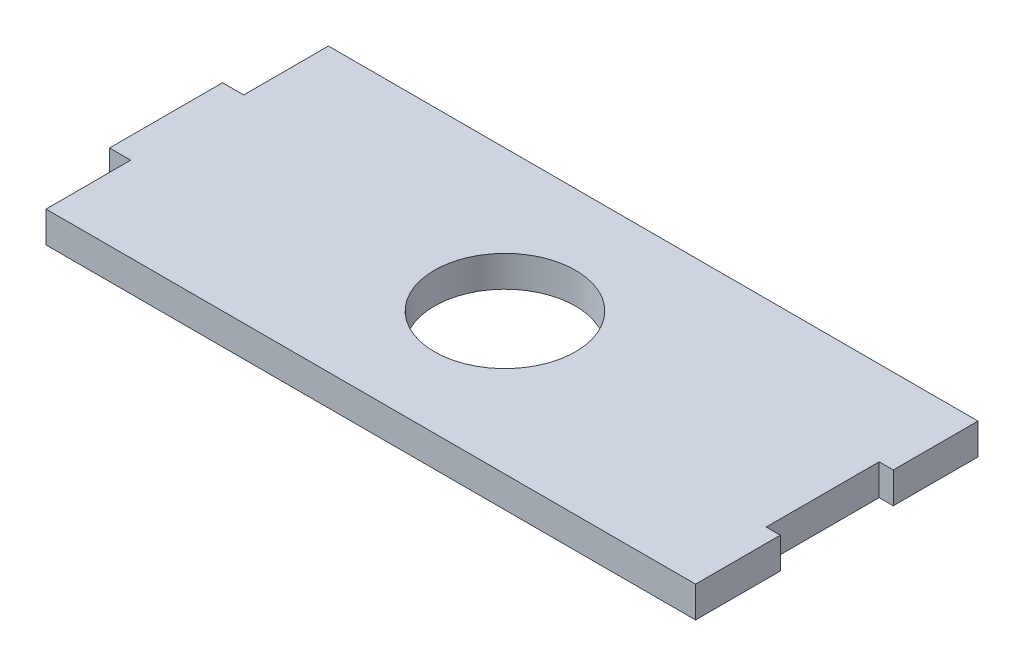
SolidWorks part; units mm, degrees
material "cardboard"
ref_plane "Front Plane" through (0, 0, 0) normal (0, 0, 1) x (1, 0, 0)
ref_plane "Top Plane" through (0, 0, 0) normal (0, 1, 0) x (1, 0, 0)
ref_plane "Right Plane" through (0, 0, 0) normal (1, 0, 0) x (0, 0, -1)
sketch "Sketch1" plane through (0, 0, 0) normal (0, 1, 0) x (1, 0, 0)
  line L0 (76.9454, 11.5977) -> (70.0953, 7.6428)
  line L1 (102.4454, -12.4023) -> (109.2956, -8.4474)
  line L2 (117.5953, 7.6428) -> (109.2956, 7.6428)
  line L3 (117.5953, -8.4474) -> (109.2956, -8.4474)
  line L4 (70.0953, 7.6428) -> (61.7956, 7.6428)
  line L5 (124.4454, 11.5977) -> (117.5953, 7.6428)
  line L6 (124.4454, -12.4023) -> (117.5953, -8.4474)
  line L7 (102.4454, 11.5977) -> (109.2956, 7.6428)
  line L8 (124.4454, 11.5977) -> (137.1954, 11.5977)
  line L9 (124.4454, -12.4023) -> (161.1954, -12.4023)
  line L10 (54.9454, 11.5977) -> (61.7956, 7.6428)
  line L11 (54.9454, -12.4023) -> (61.7956, -8.4474)
  line L12 (76.9454, -12.4023) -> (70.0953, -8.4474)
  line L13 (70.0953, -8.4474) -> (61.7956, -8.4474)
  line L14 (76.9454, 11.5977) -> (102.4454, 11.5977)
  line L15 (76.9454, -12.4023) -> (102.4454, -12.4023)
  line L16 (-12.8046, 77.3477) -> (-8.8496, 70.4976)
  line L17 (11.1954, 102.8477) -> (7.2405, 109.6979)
  line L18 (-8.8496, 117.9976) -> (-8.8496, 109.6979)
  line L19 (7.2405, 117.9976) -> (7.2405, 109.6979)
  line L20 (-8.8496, 70.4976) -> (-8.8496, 62.1979)
  line L21 (-12.8046, 124.8477) -> (-8.8496, 117.9976)
  line L22 (11.1954, 124.8477) -> (7.2405, 117.9976)
  line L23 (-12.8046, 102.8477) -> (-8.8496, 109.6979)
  line L24 (-12.8046, 124.8477) -> (-12.8046, 137.5977)
  line L25 (11.1954, 124.8477) -> (11.1954, 161.5977)
  line L26 (-12.8046, 55.3477) -> (-8.8496, 62.1979)
  line L27 (11.1954, 55.3477) -> (7.2405, 62.1979)
  line L28 (11.1954, 77.3477) -> (7.2405, 70.4976)
  line L29 (7.2405, 70.4976) -> (7.2405, 62.1979)
  line L30 (-12.8046, 77.3477) -> (-12.8046, 102.8477)
  line L31 (11.1954, 77.3477) -> (11.1954, 102.8477)
  line L32 (89.6954, 36.5977) -> (89.6954, 16.5977)
  line L33 (88.6954, 36.5977) -> (88.6954, 30.5977)
  line L34 (36.1954, 11.5977) -> (42.1954, 11.5977)
  line L35 (88.6954, 30.5977) -> (90.6954, 30.5977)
  line L36 (40.9454, 11.5977) -> (40.9454, 9.5977)
  line L37 (42.1954, 11.5977) -> (54.9454, 11.5977)
  line L38 (137.1954, 11.5977) -> (137.1954, -12.4023)
  line L39 (137.1954, 11.5977) -> (161.1954, 11.5977)
  line L40 (161.1954, 11.5977) -> (161.1954, 9.5977)
  line L41 (-29.301, 13.952) -> (-0.8046, -14.5444)
  line L42 (-29.301, 13.952) -> (-15.1588, 28.0941)
  line L43 (-0.8046, -14.5444) -> (13.3376, -0.4023)
  line L44 (-15.1588, 28.0941) -> (13.3376, -0.4023)
  line L45 (137.1954, 11.5977) -> (137.1954, 36.5977)
  line L46 (39.1954, 36.5977) -> (161.1954, 36.5977)
  line L47 (161.1954, 36.5977) -> (161.1954, 11.5977)
  line L48 (90.6954, 30.5977) -> (90.6954, 22.5977)
  line L49 (137.1954, 36.5977) -> (137.1954, 60.5977)
  line L50 (137.1954, 60.5977) -> (146.1954, 60.5977)
  line L51 (42.1954, 36.5977) -> (42.1954, 16.5977)
  line L52 (161.1954, 60.5977) -> (161.1954, 50.9197)
  line L53 (146.1954, 60.5977) -> (146.1954, 62.7977)
  line L54 (152.1954, 62.7977) -> (152.1954, 60.5977)
  line L55 (152.1954, 60.5977) -> (161.1954, 60.5977)
  line L56 (-59.8046, 137.5977) -> (-59.8046, 113.0977)
  line L57 (-39.8046, 113.0977) -> (-39.8046, 137.5977)
  line L58 (90.6954, 22.5977) -> (88.6954, 22.5977)
  line L59 (137.1954, -12.4023) -> (137.1954, -37.4023)
  line L60 (146.1954, -37.4023) -> (152.1954, -37.4023)
  line L61 (161.1954, -37.4023) -> (161.1954, -12.4023)
  line L62 (42.1954, -37.4023) -> (42.1954, -17.4023)
  line L63 (137.1954, -37.4023) -> (137.1954, -38.5823)
  line L64 (152.1954, -38.5823) -> (161.1954, -38.5823)
  line L65 (161.1954, -38.5823) -> (161.1954, -37.4023)
  line L66 (146.1954, -38.5823) -> (146.1954, -37.4023)
  line L67 (152.1954, -38.5823) -> (152.1954, -37.4023)
  line L68 (-38.9846, -138.4023) -> (-38.9846, -147.4023)
  line L69 (88.6954, 22.5977) -> (88.6954, 16.5977)
  line L70 (88.6954, 11.5977) -> (88.6954, 3.5977)
  line L71 (42.1954, -12.4023) -> (54.9454, -12.4023)
  line L72 (36.1954, -12.4023) -> (42.1954, -12.4023)
  line L73 (89.6692, 11.5977) -> (89.6692, -12.4023)
  line L74 (88.6954, 3.5977) -> (90.6954, 3.5977)
  line L75 (90.6954, 3.5977) -> (90.6954, -4.4023)
  line L76 (90.6954, -4.4023) -> (88.6954, -4.4023)
  line L77 (135.1954, 11.5977) -> (135.1954, 3.5977)
  line L78 (135.1954, 3.5977) -> (139.1954, 3.5977)
  line L79 (37.3754, 161.5977) -> (37.3754, 152.5977)
  line L80 (37.1954, 34.5977) -> (37.1954, 18.5977)
  line L81 (39.1954, 16.5977) -> (137.1954, 16.5977)
  line L82 (40.9454, 23.5977) -> (40.9454, 16.5977)
  line L83 (42.1954, 29.5977) -> (39.1954, 29.5977)
  line L84 (39.1954, 29.5977) -> (39.1954, 23.5977)
  line L85 (43.4454, 5.5977) -> (40.9454, 5.5977)
  line L86 (5.1954, -42.1523) -> (5.1954, -40.1523)
  line L87 (40.9454, -6.4023) -> (43.4454, -6.4023)
  line L88 (43.4454, 5.5977) -> (43.4454, -6.4023)
  line L89 (42.1954, 11.5977) -> (42.1954, 5.5977)
  line L90 (40.9454, 9.5977) -> (43.4454, 9.5977)
  line L91 (43.4454, 9.5977) -> (43.4454, 7.5977)
  line L92 (43.4454, 7.5977) -> (40.9454, 7.5977)
  line L93 (40.9454, 7.5977) -> (40.9454, 5.5977)
  line L94 (40.9454, -8.4023) -> (40.9454, -6.4023)
  line L95 (43.4454, -8.4023) -> (40.9454, -8.4023)
  line L96 (43.4454, -10.4023) -> (43.4454, -8.4023)
  line L97 (40.9454, -10.4023) -> (43.4454, -10.4023)
  line L98 (40.9454, -12.4023) -> (40.9454, -10.4023)
  line L99 (139.1954, 3.5977) -> (139.1954, -4.4023)
  line L100 (139.1954, -4.4023) -> (135.1954, -4.4023)
  line L101 (135.1954, -4.4023) -> (135.1954, -12.4023)
  line L102 (137.1954, 13.5977) -> (145.1954, 13.5977)
  line L103 (145.1954, 13.5977) -> (145.1954, 9.5977)
  line L104 (145.1954, 9.5977) -> (153.1954, 9.5977)
  line L105 (153.1954, 9.5977) -> (153.1954, 13.5977)
  line L106 (153.1954, 13.5977) -> (161.1954, 13.5977)
  line L107 (135.6954, 36.5977) -> (135.6954, 30.5977)
  line L108 (135.6954, 30.5977) -> (138.6954, 30.5977)
  line L109 (138.6954, 30.5977) -> (138.6954, 22.5977)
  line L110 (138.6954, 22.5977) -> (135.6954, 22.5977)
  line L111 (135.6954, 22.5977) -> (135.6954, 16.5977)
  line L112 (88.6954, -4.4023) -> (88.6954, -12.4023)
  line L113 (88.6954, -23.4023) -> (88.6954, -17.4023)
  line L114 (89.6954, -37.4023) -> (89.6954, -17.4023)
  line L115 (90.6954, -23.4023) -> (88.6954, -23.4023)
  line L116 (90.6954, -31.4023) -> (90.6954, -23.4023)
  line L117 (153.1954, -14.4023) -> (161.1954, -14.4023)
  line L118 (153.1954, -10.4023) -> (153.1954, -14.4023)
  line L119 (145.1954, -10.4023) -> (153.1954, -10.4023)
  line L120 (145.1954, -14.4023) -> (145.1954, -10.4023)
  line L121 (137.1954, -14.4023) -> (145.1954, -14.4023)
  line L122 (135.6954, -23.4023) -> (135.6954, -17.4023)
  line L123 (138.6954, -23.4023) -> (135.6954, -23.4023)
  line L124 (40.9454, 36.5977) -> (40.9454, 29.5977)
  line L125 (42.1954, 23.5977) -> (39.1954, 23.5977)
  line L126 (137.1954, -37.4023) -> (39.1954, -37.4023)
  line L127 (37.1954, -35.4023) -> (37.1954, -19.4023)
  line L128 (39.1954, -17.4023) -> (137.1954, -17.4023)
  line L129 (138.6954, -31.4023) -> (138.6954, -23.4023)
  line L130 (135.6954, -31.4023) -> (138.6954, -31.4023)
  line L131 (135.6954, -37.4023) -> (135.6954, -31.4023)
  line L132 (88.6954, -31.4023) -> (90.6954, -31.4023)
  line L133 (88.6954, -37.4023) -> (88.6954, -31.4023)
  line L134 (137.1954, 38.5977) -> (145.1954, 38.5977)
  line L135 (145.1954, 38.5977) -> (145.1954, 34.5977)
  line L136 (145.1954, 34.5977) -> (153.1954, 34.5977)
  line L137 (153.1954, 34.5977) -> (153.1954, 38.5977)
  line L138 (153.1954, 38.5977) -> (161.1954, 38.5977)
  line L139 (-45.3046, 133.3477) -> (-45.3046, 117.3477)
  line L140 (-56.8046, 133.3477) -> (-54.3046, 133.3477)
  line L141 (-56.8046, 133.3477) -> (-56.8046, 117.3477)
  line L142 (-56.8046, 117.3477) -> (-54.3046, 117.3477)
  line L143 (-54.3046, 133.3477) -> (-54.3046, 117.3477)
  line L144 (40.9454, -24.4023) -> (40.9454, -17.4023)
  line L145 (42.1954, -24.4023) -> (39.1954, -24.4023)
  line L146 (39.1954, -30.4023) -> (39.1954, -24.4023)
  line L147 (42.1954, -30.4023) -> (39.1954, -30.4023)
  line L148 (40.9454, -37.4023) -> (40.9454, -30.4023)
  line L149 (196.1954, 4.5977) -> (196.1954, -5.4023)
  line L150 (191.1954, 9.5977) -> (161.1954, 9.5977)
  line L151 (191.1954, -10.4023) -> (161.1954, -10.4023)
  line L152 (191.1954, 9.5977) -> (196.1954, 4.5977)
  line L153 (196.1954, -5.4023) -> (191.1954, -10.4023)
  line L154 (161.1954, -10.4023) -> (161.1954, -12.4023)
  line L155 (137.1954, 62.7977) -> (146.1954, 62.7977)
  line L156 (137.1954, 62.7977) -> (137.1954, 64.7977)
  line L157 (137.1954, 64.7977) -> (161.1954, 64.7977)
  line L158 (161.1954, 64.7977) -> (161.1954, 62.7977)
  line L159 (152.1954, 62.7977) -> (161.1954, 62.7977)
  line L160 (-42.8046, 117.3477) -> (-45.3046, 117.3477)
  line L161 (-42.8046, 133.3477) -> (-42.8046, 117.3477)
  line L162 (-42.8046, 133.3477) -> (-45.3046, 133.3477)
  line L163 (154.5954, 50.9197) -> (161.1954, 50.9197)
  line L164 (154.5954, 50.9197) -> (154.5954, 46.4197)
  line L165 (154.5954, 46.4197) -> (161.1954, 46.4197)
  line L166 (161.1954, 46.4197) -> (161.1954, 36.5977)
  line L167 (11.1954, -78.1523) -> (7.2405, -71.3021)
  line L168 (-12.8046, -103.6523) -> (-8.8496, -110.5024)
  line L169 (7.2405, -118.8021) -> (7.2405, -110.5024)
  line L170 (11.1954, -37.4023) -> (11.1954, -43.4023)
  line L171 (11.1954, -42.1523) -> (9.1954, -42.1523)
  line L172 (11.1954, -43.4023) -> (11.1954, -56.1523)
  line L173 (-8.8496, -118.8021) -> (-8.8496, -110.5024)
  line L174 (7.2405, -71.3021) -> (7.2405, -63.0024)
  line L175 (11.1954, -125.6523) -> (7.2405, -118.8021)
  line L176 (-12.8046, -125.6523) -> (-8.8496, -118.8021)
  line L177 (11.1954, -103.6523) -> (7.2405, -110.5024)
  line L178 (11.1954, -125.6523) -> (11.1954, -138.4023)
  line L179 (-12.8046, -125.6523) -> (-12.8046, -162.4023)
  line L180 (11.1954, -56.1523) -> (7.2405, -63.0024)
  line L181 (-12.8046, -56.1523) -> (-8.8496, -63.0024)
  line L182 (36.1954, -43.4023) -> (16.1954, -43.4023)
  line L183 (-12.8046, -78.1523) -> (-8.8496, -71.3021)
  line L184 (-8.8496, -71.3021) -> (-8.8496, -63.0024)
  line L185 (11.1954, -78.1523) -> (11.1954, -103.6523)
  line L186 (-12.8046, -78.1523) -> (-12.8046, -103.6523)
  line L187 (36.1954, -90.9023) -> (16.1954, -90.9023)
  line L188 (36.1954, -89.9023) -> (30.1954, -89.9023)
  line L189 (30.1954, -89.9023) -> (30.1954, -91.9023)
  line L190 (11.1954, -138.4023) -> (-12.8046, -138.4023)
  line L191 (11.1954, -138.4023) -> (11.1954, -162.4023)
  line L192 (11.1954, -162.4023) -> (9.1954, -162.4023)
  line L193 (11.1954, -138.4023) -> (36.1954, -138.4023)
  line L194 (36.1954, -40.4023) -> (36.1954, -162.4023)
  line L195 (-37.8046, -43.4023) -> (-17.8046, -43.4023)
  line L196 (36.1954, -162.4023) -> (11.1954, -162.4023)
  line L197 (30.1954, -91.9023) -> (22.1954, -91.9023)
  line L198 (36.1954, -138.4023) -> (60.1954, -138.4023)
  line L199 (60.1954, -138.4023) -> (60.1954, -147.4023)
  line L200 (60.1954, -162.4023) -> (50.5174, -162.4023)
  line L201 (60.1954, -147.4023) -> (62.3954, -147.4023)
  line L202 (62.3954, -153.4023) -> (60.1954, -153.4023)
  line L203 (60.1954, -153.4023) -> (60.1954, -162.4023)
  line L204 (-12.8046, -43.4023) -> (-12.8046, -56.1523)
  line L205 (-12.8046, -37.4023) -> (-12.8046, -43.4023)
  line L206 (22.1954, -91.9023) -> (22.1954, -89.9023)
  line L207 (-12.8046, -138.4023) -> (-37.8046, -138.4023)
  line L208 (-37.8046, -147.4023) -> (-37.8046, -153.4023)
  line L209 (37.3754, 146.5977) -> (37.3754, 137.5977)
  line L210 (34.1954, -38.4023) -> (18.1954, -38.4023)
  line L211 (16.1954, -40.4023) -> (16.1954, -138.4023)
  line L212 (23.1954, -42.1523) -> (16.1954, -42.1523)
  line L213 (29.1954, -43.4023) -> (29.1954, -40.4023)
  line L214 (29.1954, -40.4023) -> (23.1954, -40.4023)
  line L215 (5.1954, -44.6523) -> (5.1954, -42.1523)
  line L216 (-37.8046, -162.4023) -> (-12.8046, -162.4023)
  line L217 (-6.8046, -42.1523) -> (-6.8046, -44.6523)
  line L218 (5.1954, -44.6523) -> (-6.8046, -44.6523)
  line L219 (11.1954, -43.4023) -> (5.1954, -43.4023)
  line L220 (9.1954, -42.1523) -> (9.1954, -44.6523)
  line L221 (9.1954, -44.6523) -> (7.1954, -44.6523)
  line L222 (7.1954, -44.6523) -> (7.1954, -42.1523)
  line L223 (7.1954, -42.1523) -> (5.1954, -42.1523)
  line L224 (-8.8046, -42.1523) -> (-6.8046, -42.1523)
  line L225 (-8.8046, -44.6523) -> (-8.8046, -42.1523)
  line L226 (-10.8046, -44.6523) -> (-8.8046, -44.6523)
  line L227 (-10.8046, -42.1523) -> (-10.8046, -44.6523)
  line L228 (-12.8046, -42.1523) -> (-10.8046, -42.1523)
  line L229 (-37.8046, -138.4023) -> (-38.9846, -138.4023)
  line L230 (-38.9846, -153.4023) -> (-38.9846, -162.4023)
  line L231 (-38.9846, -162.4023) -> (-37.8046, -162.4023)
  line L232 (-38.9846, -147.4023) -> (-37.8046, -147.4023)
  line L233 (-38.9846, -153.4023) -> (-37.8046, -153.4023)
  line L234 (-162.8046, 37.7777) -> (-153.8046, 37.7777)
  line L235 (22.1954, -89.9023) -> (16.1954, -89.9023)
  line L236 (11.1954, -89.9023) -> (3.1954, -89.9023)
  line L237 (11.1954, -90.8761) -> (-12.8046, -90.8761)
  line L238 (3.1954, -89.9023) -> (3.1954, -91.9023)
  line L239 (3.1954, -91.9023) -> (-4.8046, -91.9023)
  line L240 (-4.8046, -91.9023) -> (-4.8046, -89.9023)
  line L241 (11.1954, -136.4023) -> (3.1954, -136.4023)
  line L242 (3.1954, -136.4023) -> (3.1954, -140.4023)
  line L243 (3.1954, -140.4023) -> (-4.8046, -140.4023)
  line L244 (-4.8046, -140.4023) -> (-4.8046, -136.4023)
  line L245 (-4.8046, -136.4023) -> (-12.8046, -136.4023)
  line L246 (13.1954, -138.4023) -> (13.1954, -146.4023)
  line L247 (13.1954, -146.4023) -> (9.1954, -146.4023)
  line L248 (9.1954, -146.4023) -> (9.1954, -154.4023)
  line L249 (9.1954, -154.4023) -> (13.1954, -154.4023)
  line L250 (13.1954, -154.4023) -> (13.1954, -162.4023)
  line L251 (36.1954, -136.9023) -> (30.1954, -136.9023)
  line L252 (30.1954, -136.9023) -> (30.1954, -139.9023)
  line L253 (30.1954, -139.9023) -> (22.1954, -139.9023)
  line L254 (36.1954, -42.1523) -> (29.1954, -42.1523)
  line L255 (23.1954, -43.4023) -> (23.1954, -40.4023)
  line L256 (-37.8046, -138.4023) -> (-37.8046, -40.4023)
  line L257 (-35.8046, -38.4023) -> (-19.8046, -38.4023)
  line L258 (-17.8046, -40.4023) -> (-17.8046, -138.4023)
  line L259 (22.1954, -139.9023) -> (22.1954, -136.9023)
  line L260 (22.1954, -136.9023) -> (16.1954, -136.9023)
  line L261 (-4.8046, -89.9023) -> (-12.8046, -89.9023)
  line L262 (-23.8046, -89.9023) -> (-17.8046, -89.9023)
  line L263 (-37.8046, -90.9023) -> (-17.8046, -90.9023)
  line L264 (-23.8046, -91.9023) -> (-23.8046, -89.9023)
  line L265 (-31.8046, -91.9023) -> (-23.8046, -91.9023)
  line L266 (-14.8046, -154.4023) -> (-14.8046, -162.4023)
  line L267 (-10.8046, -154.4023) -> (-14.8046, -154.4023)
  line L268 (-10.8046, -146.4023) -> (-10.8046, -154.4023)
  line L269 (-14.8046, -146.4023) -> (-10.8046, -146.4023)
  line L270 (-14.8046, -138.4023) -> (-14.8046, -146.4023)
  line L271 (-23.8046, -136.9023) -> (-17.8046, -136.9023)
  line L272 (-23.8046, -139.9023) -> (-23.8046, -136.9023)
  line L273 (-31.8046, -139.9023) -> (-23.8046, -139.9023)
  line L274 (-24.8046, -42.1523) -> (-17.8046, -42.1523)
  line L275 (-24.8046, -43.4023) -> (-24.8046, -40.4023)
  line L276 (-30.8046, -40.4023) -> (-24.8046, -40.4023)
  line L277 (-30.8046, -43.4023) -> (-30.8046, -40.4023)
  line L278 (-37.8046, -42.1523) -> (-30.8046, -42.1523)
  line L279 (-31.8046, -136.9023) -> (-31.8046, -139.9023)
  line L280 (-37.8046, -136.9023) -> (-31.8046, -136.9023)
  line L281 (-31.8046, -89.9023) -> (-31.8046, -91.9023)
  line L282 (-37.8046, -89.9023) -> (-31.8046, -89.9023)
  line L283 (38.1954, -138.4023) -> (38.1954, -146.4023)
  line L284 (38.1954, -146.4023) -> (34.1954, -146.4023)
  line L285 (34.1954, -146.4023) -> (34.1954, -154.4023)
  line L286 (34.1954, -154.4023) -> (38.1954, -154.4023)
  line L287 (38.1954, -154.4023) -> (38.1954, -162.4023)
  line L288 (4.1954, -197.4023) -> (-5.8046, -197.4023)
  line L289 (9.1954, -192.4023) -> (9.1954, -162.4023)
  line L290 (-10.8046, -192.4023) -> (-10.8046, -162.4023)
  line L291 (9.1954, -192.4023) -> (4.1954, -197.4023)
  line L292 (-5.8046, -197.4023) -> (-10.8046, -192.4023)
  line L293 (-10.8046, -162.4023) -> (-12.8046, -162.4023)
  line L294 (62.3954, -138.4023) -> (62.3954, -147.4023)
  line L295 (62.3954, -138.4023) -> (64.3954, -138.4023)
  line L296 (64.3954, -138.4023) -> (64.3954, -162.4023)
  line L297 (64.3954, -162.4023) -> (62.3954, -162.4023)
  line L298 (62.3954, -153.4023) -> (62.3954, -162.4023)
  line L299 (-37.8046, -12.4023) -> (-43.8046, -12.4023)
  line L300 (-42.5546, -12.4023) -> (-42.5546, -10.4023)
  line L301 (-43.8046, -12.4023) -> (-56.5546, -12.4023)
  line L302 (50.5174, -155.8023) -> (50.5174, -162.4023)
  line L303 (50.5174, -155.8023) -> (46.0174, -155.8023)
  line L304 (-43.8046, -37.4023) -> (-43.8046, -17.4023)
  line L305 (46.0174, -155.8023) -> (46.0174, -162.4023)
  line L306 (46.0174, -162.4023) -> (36.1954, -162.4023)
  line L307 (-78.5546, -12.4023) -> (-71.7044, -8.4474)
  line L308 (-104.0546, 11.5977) -> (-110.9047, 7.6428)
  line L309 (-119.2044, -8.4474) -> (-110.9047, -8.4474)
  line L310 (-119.2044, 7.6428) -> (-110.9047, 7.6428)
  line L311 (-71.7044, -8.4474) -> (-63.4047, -8.4474)
  line L312 (-126.0546, -12.4023) -> (-119.2044, -8.4474)
  line L313 (-126.0546, 11.5977) -> (-119.2044, 7.6428)
  line L314 (-104.0546, -12.4023) -> (-110.9047, -8.4474)
  line L315 (-126.0546, -12.4023) -> (-138.8046, -12.4023)
  line L316 (-43.8046, 36.5977) -> (-43.8046, 16.5977)
  line L317 (-126.0546, 11.5977) -> (-162.8046, 11.5977)
  line L318 (-56.5546, -12.4023) -> (-63.4047, -8.4474)
  line L319 (-56.5546, 11.5977) -> (-63.4047, 7.6428)
  line L320 (-78.5546, 11.5977) -> (-71.7044, 7.6428)
  line L321 (-71.7044, 7.6428) -> (-63.4047, 7.6428)
  line L322 (-78.5546, -12.4023) -> (-104.0546, -12.4023)
  line L323 (-78.5546, 11.5977) -> (-104.0546, 11.5977)
  line L324 (-91.3046, -37.4023) -> (-91.3046, -17.4023)
  line L325 (-43.8046, 11.5977) -> (-56.5546, 11.5977)
  line L326 (-37.8046, 11.5977) -> (-43.8046, 11.5977)
  line L327 (-90.3046, -37.4023) -> (-90.3046, -31.4023)
  line L328 (-90.3046, -31.4023) -> (-92.3046, -31.4023)
  line L329 (-138.8046, -12.4023) -> (-138.8046, 11.5977)
  line L330 (-138.8046, -12.4023) -> (-162.8046, -12.4023)
  line L331 (-162.8046, -12.4023) -> (-162.8046, -10.4023)
  line L332 (-138.8046, -12.4023) -> (-138.8046, -37.4023)
  line L333 (137.1954, -38.5823) -> (146.1954, -38.5823)
  line L334 (-38.8046, -35.4023) -> (-38.8046, -19.4023)
  line L335 (-40.8046, -17.4023) -> (-138.8046, -17.4023)
  line L336 (-42.5546, -24.4023) -> (-42.5546, -17.4023)
  line L337 (-43.8046, -30.4023) -> (-40.8046, -30.4023)
  line L338 (-40.8046, -30.4023) -> (-40.8046, -24.4023)
  line L339 (-45.0546, -6.4023) -> (-42.5546, -6.4023)
  line L340 (-40.8046, -37.4023) -> (-162.8046, -37.4023)
  line L341 (-42.5546, 5.5977) -> (-45.0546, 5.5977)
  line L342 (-45.0546, -6.4023) -> (-45.0546, 5.5977)
  line L343 (-43.8046, -12.4023) -> (-43.8046, -6.4023)
  line L344 (-42.5546, -10.4023) -> (-45.0546, -10.4023)
  line L345 (-45.0546, -10.4023) -> (-45.0546, -8.4023)
  line L346 (-45.0546, -8.4023) -> (-42.5546, -8.4023)
  line L347 (-42.5546, -8.4023) -> (-42.5546, -6.4023)
  line L348 (-42.5546, 7.5977) -> (-42.5546, 5.5977)
  line L349 (-45.0546, 7.5977) -> (-42.5546, 7.5977)
  line L350 (-45.0546, 9.5977) -> (-45.0546, 7.5977)
  line L351 (-42.5546, 9.5977) -> (-45.0546, 9.5977)
  line L352 (-42.5546, 11.5977) -> (-42.5546, 9.5977)
  line L353 (-162.8046, -37.4023) -> (-162.8046, -12.4023)
  line L354 (-92.3046, -31.4023) -> (-92.3046, -23.4023)
  line L355 (-138.8046, -37.4023) -> (-138.8046, -61.4023)
  line L356 (-138.8046, -61.4023) -> (-147.8046, -61.4023)
  line L357 (-162.8046, -61.4023) -> (-162.8046, -51.7243)
  line L358 (-147.8046, -61.4023) -> (-147.8046, -63.6023)
  line L359 (-153.8046, -63.6023) -> (-153.8046, -61.4023)
  line L360 (-153.8046, -61.4023) -> (-162.8046, -61.4023)
  line L361 (-92.3046, -23.4023) -> (-90.3046, -23.4023)
  line L362 (-138.8046, 11.5977) -> (-138.8046, 36.5977)
  line L363 (-147.8046, 36.5977) -> (-153.8046, 36.5977)
  line L364 (-162.8046, 36.5977) -> (-162.8046, 11.5977)
  line L365 (-138.8046, 36.5977) -> (-138.8046, 37.7777)
  line L366 (-162.8046, 37.7777) -> (-162.8046, 36.5977)
  line L367 (-147.8046, 37.7777) -> (-147.8046, 36.5977)
  line L368 (-153.8046, 37.7777) -> (-153.8046, 36.5977)
  line L369 (-147.8046, 37.7777) -> (-138.8046, 37.7777)
  line L370 (-90.3046, -23.4023) -> (-90.3046, -17.4023)
  line L371 (-90.3046, -12.4023) -> (-90.3046, -4.4023)
  line L372 (-91.2784, -12.4023) -> (-91.2784, 11.5977)
  line L373 (-90.3046, -4.4023) -> (-92.3046, -4.4023)
  line L374 (-42.5546, -37.4023) -> (-42.5546, -30.4023)
  line L375 (-43.8046, -24.4023) -> (-40.8046, -24.4023)
  line L376 (-138.8046, 36.5977) -> (-40.8046, 36.5977)
  line L377 (-38.8046, 34.5977) -> (-38.8046, 18.5977)
  line L378 (-40.8046, 16.5977) -> (-138.8046, 16.5977)
  line L379 (-92.3046, -4.4023) -> (-92.3046, 3.5977)
  line L380 (-92.3046, 3.5977) -> (-90.3046, 3.5977)
  line L381 (-136.8046, -12.4023) -> (-136.8046, -4.4023)
  line L382 (-136.8046, -4.4023) -> (-140.8046, -4.4023)
  line L383 (-140.8046, -4.4023) -> (-140.8046, 3.5977)
  line L384 (-140.8046, 3.5977) -> (-136.8046, 3.5977)
  line L385 (-136.8046, 3.5977) -> (-136.8046, 11.5977)
  line L386 (-138.8046, -14.4023) -> (-146.8046, -14.4023)
  line L387 (-146.8046, -14.4023) -> (-146.8046, -10.4023)
  line L388 (-146.8046, -10.4023) -> (-154.8046, -10.4023)
  line L389 (-154.8046, -10.4023) -> (-154.8046, -14.4023)
  line L390 (-154.8046, -14.4023) -> (-162.8046, -14.4023)
  line L391 (-137.3046, -37.4023) -> (-137.3046, -31.4023)
  line L392 (-37.8046, 90.0977) -> (-17.8046, 90.0977)
  line L393 (-37.8046, 89.0977) -> (-31.8046, 89.0977)
  line L394 (-42.5546, 23.5977) -> (-42.5546, 16.5977)
  line L395 (-43.8046, 23.5977) -> (-40.8046, 23.5977)
  line L396 (-40.8046, 29.5977) -> (-40.8046, 23.5977)
  line L397 (-43.8046, 29.5977) -> (-40.8046, 29.5977)
  line L398 (-42.5546, 36.5977) -> (-42.5546, 29.5977)
  line L399 (-137.3046, -31.4023) -> (-140.3046, -31.4023)
  line L400 (-140.3046, -31.4023) -> (-140.3046, -23.4023)
  line L401 (-140.3046, -23.4023) -> (-137.3046, -23.4023)
  line L402 (-137.3046, -23.4023) -> (-137.3046, -17.4023)
  line L403 (-90.3046, 3.5977) -> (-90.3046, 11.5977)
  line L404 (-90.3046, 22.5977) -> (-90.3046, 16.5977)
  line L405 (-91.3046, 36.5977) -> (-91.3046, 16.5977)
  line L406 (-92.3046, 22.5977) -> (-90.3046, 22.5977)
  line L407 (-92.3046, 30.5977) -> (-92.3046, 22.5977)
  line L408 (-154.8046, 13.5977) -> (-162.8046, 13.5977)
  line L409 (-154.8046, 9.5977) -> (-154.8046, 13.5977)
  line L410 (-146.8046, 9.5977) -> (-154.8046, 9.5977)
  line L411 (-146.8046, 13.5977) -> (-146.8046, 9.5977)
  line L412 (-138.8046, 13.5977) -> (-146.8046, 13.5977)
  line L413 (-137.3046, 22.5977) -> (-137.3046, 16.5977)
  line L414 (-140.3046, 22.5977) -> (-137.3046, 22.5977)
  line L415 (-140.3046, 30.5977) -> (-140.3046, 22.5977)
  line L416 (-137.3046, 30.5977) -> (-140.3046, 30.5977)
  line L417 (-137.3046, 36.5977) -> (-137.3046, 30.5977)
  line L418 (-90.3046, 30.5977) -> (-92.3046, 30.5977)
  line L419 (-90.3046, 36.5977) -> (-90.3046, 30.5977)
  line L420 (-138.8046, -39.4023) -> (-146.8046, -39.4023)
  line L421 (-146.8046, -39.4023) -> (-146.8046, -35.4023)
  line L422 (-146.8046, -35.4023) -> (-154.8046, -35.4023)
  line L423 (-154.8046, -35.4023) -> (-154.8046, -39.4023)
  line L424 (-154.8046, -39.4023) -> (-162.8046, -39.4023)
  line L425 (-12.8046, 41.3477) -> (-10.8046, 41.3477)
  line L426 (-31.8046, 89.0977) -> (-31.8046, 91.0977)
  line L427 (-12.8046, 137.5977) -> (11.1954, 137.5977)
  line L428 (-12.8046, 137.5977) -> (-12.8046, 161.5977)
  line L429 (-12.8046, 161.5977) -> (-10.8046, 161.5977)
  line L430 (-12.8046, 137.5977) -> (-37.8046, 137.5977)
  line L431 (-37.8046, 137.5977) -> (-37.8046, 161.5977)
  line L432 (-37.8046, 161.5977) -> (-12.8046, 161.5977)
  line L433 (-37.8046, 137.5977) -> (-37.8046, 42.5977)
  line L434 (-37.8046, 42.5977) -> (-17.8046, 42.5977)
  line L435 (-17.8046, 42.5977) -> (-17.8046, 137.5977)
  line L436 (-31.8046, 91.0977) -> (-23.8046, 91.0977)
  line L437 (-37.8046, 137.5977) -> (-61.8046, 137.5977)
  line L438 (-61.8046, 137.5977) -> (-61.8046, 146.5977)
  line L439 (-61.8046, 161.5977) -> (-52.1265, 161.5977)
  line L440 (-61.8046, 146.5977) -> (-64.0046, 146.5977)
  line L441 (-64.0046, 152.5977) -> (-61.8046, 152.5977)
  line L442 (-61.8046, 152.5977) -> (-61.8046, 161.5977)
  line L443 (-59.8046, 113.0977) -> (-39.8046, 113.0977)
  line L444 (36.1954, 42.5977) -> (16.1954, 42.5977)
  line L445 (-23.8046, 91.0977) -> (-23.8046, 89.0977)
  line L446 (36.1954, 137.5977) -> (36.1954, 42.5977)
  line L447 (16.1954, 42.5977) -> (16.1954, 137.5977)
  line L448 (11.1954, 137.5977) -> (36.1954, 137.5977)
  line L449 (36.1954, 146.5977) -> (36.1954, 152.5977)
  line L450 (36.1954, 161.5977) -> (11.1954, 161.5977)
  line L451 (11.1954, 36.5977) -> (11.1954, 55.3477)
  line L452 (36.1954, 137.5977) -> (37.3754, 137.5977)
  line L453 (37.3754, 161.5977) -> (36.1954, 161.5977)
  line L454 (37.3754, 146.5977) -> (36.1954, 146.5977)
  line L455 (37.3754, 152.5977) -> (36.1954, 152.5977)
  line L456 (-37.8046, 42.5977) -> (-37.8046, 39.5977)
  line L457 (-35.8046, 37.5977) -> (-19.8046, 37.5977)
  line L458 (-17.8046, 39.5977) -> (-17.8046, 42.5977)
  line L459 (34.1954, 37.5977) -> (18.1954, 37.5977)
  line L460 (16.1954, 39.5977) -> (16.1954, 42.5977)
  line L461 (-6.8046, 43.8477) -> (-6.8046, 41.3477)
  line L462 (-23.8046, 89.0977) -> (-17.8046, 89.0977)
  line L463 (5.1954, 41.3477) -> (5.1954, 43.8477)
  line L464 (-6.8046, 43.8477) -> (5.1954, 43.8477)
  line L465 (-12.8046, 42.5977) -> (-6.8046, 42.5977)
  line L466 (-10.8046, 41.3477) -> (-10.8046, 43.8477)
  line L467 (-10.8046, 43.8477) -> (-8.8046, 43.8477)
  line L468 (-8.8046, 43.8477) -> (-8.8046, 41.3477)
  line L469 (-8.8046, 41.3477) -> (-6.8046, 41.3477)
  line L470 (7.1954, 41.3477) -> (5.1954, 41.3477)
  line L471 (7.1954, 43.8477) -> (7.1954, 41.3477)
  line L472 (9.1954, 43.8477) -> (7.1954, 43.8477)
  line L473 (9.1954, 41.3477) -> (9.1954, 43.8477)
  line L474 (11.1954, 41.3477) -> (9.1954, 41.3477)
  line L475 (-12.8046, 89.0977) -> (-4.8046, 89.0977)
  line L476 (-12.8046, 90.0715) -> (11.1954, 90.0715)
  line L477 (-4.8046, 89.0977) -> (-4.8046, 91.0977)
  line L478 (-4.8046, 91.0977) -> (3.1954, 91.0977)
  line L479 (3.1954, 91.0977) -> (3.1954, 89.0977)
  line L480 (-12.8046, 135.5977) -> (-4.8046, 135.5977)
  line L481 (-4.8046, 135.5977) -> (-4.8046, 139.5977)
  line L482 (-4.8046, 139.5977) -> (3.1954, 139.5977)
  line L483 (3.1954, 139.5977) -> (3.1954, 135.5977)
  line L484 (3.1954, 135.5977) -> (11.1954, 135.5977)
  line L485 (-14.8046, 137.5977) -> (-14.8046, 145.5977)
  line L486 (-14.8046, 145.5977) -> (-10.8046, 145.5977)
  line L487 (-10.8046, 145.5977) -> (-10.8046, 153.5977)
  line L488 (-10.8046, 153.5977) -> (-14.8046, 153.5977)
  line L489 (-14.8046, 153.5977) -> (-14.8046, 161.5977)
  line L490 (-37.8046, 136.0977) -> (-31.8046, 136.0977)
  line L491 (-31.8046, 136.0977) -> (-31.8046, 139.0977)
  line L492 (-31.8046, 139.0977) -> (-23.8046, 139.0977)
  line L493 (-23.8046, 139.0977) -> (-23.8046, 136.0977)
  line L494 (-23.8046, 136.0977) -> (-17.8046, 136.0977)
  line L495 (3.1954, 89.0977) -> (11.1954, 89.0977)
  line L496 (22.1954, 89.0977) -> (16.1954, 89.0977)
  line L497 (36.1954, 90.0977) -> (16.1954, 90.0977)
  line L498 (22.1954, 91.0977) -> (22.1954, 89.0977)
  line L499 (30.1954, 91.0977) -> (22.1954, 91.0977)
  line L500 (-37.8046, 41.3477) -> (-30.8046, 41.3477)
  line L501 (29.1954, 39.5977) -> (23.1954, 39.5977)
  line L502 (23.1954, 41.3477) -> (16.1954, 41.3477)
  line L503 (-30.8046, 42.5977) -> (-30.8046, 39.5977)
  line L504 (-24.8046, 41.3477) -> (-17.8046, 41.3477)
  line L505 (13.1954, 153.5977) -> (13.1954, 161.5977)
  line L506 (9.1954, 153.5977) -> (13.1954, 153.5977)
  line L507 (9.1954, 145.5977) -> (9.1954, 153.5977)
  line L508 (13.1954, 145.5977) -> (9.1954, 145.5977)
  line L509 (13.1954, 137.5977) -> (13.1954, 145.5977)
  line L510 (22.1954, 136.0977) -> (16.1954, 136.0977)
  line L511 (22.1954, 139.0977) -> (22.1954, 136.0977)
  line L512 (30.1954, 139.0977) -> (22.1954, 139.0977)
  line L513 (30.1954, 136.0977) -> (30.1954, 139.0977)
  line L514 (36.1954, 136.0977) -> (30.1954, 136.0977)
  line L515 (30.1954, 89.0977) -> (30.1954, 91.0977)
  line L516 (36.1954, 89.0977) -> (30.1954, 89.0977)
  line L517 (11.1954, 36.5977) -> (20.1599, 27.6332)
  line L518 (36.1954, -12.4023) -> (27.231, -21.3668)
  line L519 (-12.8046, -37.4023) -> (-21.769, -28.4378)
  line L520 (23.1954, 42.5977) -> (23.1954, 39.5977)
  line L521 (-24.8046, 42.5977) -> (-24.8046, 39.5977)
  line L522 (29.1954, 42.5977) -> (29.1954, 39.5977)
  line L523 (36.1954, 41.3477) -> (29.1954, 41.3477)
  line L524 (-39.8046, 137.5977) -> (-39.8046, 145.5977)
  line L525 (-39.8046, 145.5977) -> (-35.8046, 145.5977)
  line L526 (-35.8046, 145.5977) -> (-35.8046, 153.5977)
  line L527 (-35.8046, 153.5977) -> (-39.8046, 153.5977)
  line L528 (-39.8046, 153.5977) -> (-39.8046, 161.5977)
  line L529 (-59.8046, 136.0977) -> (-52.8046, 136.0977)
  line L530 (-52.8046, 136.0977) -> (-52.8046, 139.0977)
  line L531 (-52.8046, 139.0977) -> (-46.8046, 139.0977)
  line L532 (-46.8046, 139.0977) -> (-46.8046, 136.0977)
  line L533 (-46.8046, 136.0977) -> (-39.8046, 136.0977)
  line L534 (-12.8046, 36.5977) -> (-12.8046, 55.3477)
  line L535 (42.1954, -6.4023) -> (42.1954, -12.4023)
  line L536 (5.1954, 42.5977) -> (11.1954, 42.5977)
  line L537 (-43.8046, 5.5977) -> (-43.8046, 11.5977)
  line L538 (-6.8046, -43.4023) -> (-12.8046, -43.4023)
  line L539 (-5.8046, 196.5977) -> (4.1954, 196.5977)
  line L540 (-10.8046, 191.5977) -> (-10.8046, 161.5977)
  line L541 (9.1954, 191.5977) -> (9.1954, 161.5977)
  line L542 (-10.8046, 191.5977) -> (-5.8046, 196.5977)
  line L543 (4.1954, 196.5977) -> (9.1954, 191.5977)
  line L544 (132.9454, 55.5977) -> (116.9454, 55.5977)
  line L545 (132.9454, 55.5977) -> (132.9454, 53.0977)
  line L546 (-197.8046, -5.4023) -> (-197.8046, 4.5977)
  line L547 (-192.8046, -10.4023) -> (-162.8046, -10.4023)
  line L548 (-192.8046, 9.5977) -> (-162.8046, 9.5977)
  line L549 (-192.8046, -10.4023) -> (-197.8046, -5.4023)
  line L550 (-197.8046, 4.5977) -> (-192.8046, 9.5977)
  line L551 (-162.8046, 9.5977) -> (-162.8046, 11.5977)
  line L552 (-138.8046, -63.6023) -> (-147.8046, -63.6023)
  line L553 (-138.8046, -63.6023) -> (-138.8046, -65.6023)
  line L554 (-138.8046, -65.6023) -> (-162.8046, -65.6023)
  line L555 (-162.8046, -65.6023) -> (-162.8046, -63.6023)
  line L556 (9.1954, 161.5977) -> (11.1954, 161.5977)
  line L557 (-153.8046, -63.6023) -> (-162.8046, -63.6023)
  line L558 (132.9454, 53.0977) -> (116.9454, 53.0977)
  line L559 (116.9454, 55.5977) -> (116.9454, 53.0977)
  line L560 (132.9454, 44.0977) -> (116.9454, 44.0977)
  line L561 (132.9454, 41.5977) -> (132.9454, 44.0977)
  line L562 (132.9454, 41.5977) -> (116.9454, 41.5977)
  line L563 (116.9454, 41.5977) -> (116.9454, 44.0977)
  line L564 (135.6954, 58.5977) -> (135.6954, 51.5977)
  line L565 (135.6954, 51.5977) -> (138.6954, 51.5977)
  line L566 (-156.2046, -51.7243) -> (-162.8046, -51.7243)
  line L567 (-156.2046, -51.7243) -> (-156.2046, -47.2243)
  line L568 (-156.2046, -47.2243) -> (-162.8046, -47.2243)
  line L569 (-64.0046, 137.5977) -> (-64.0046, 146.5977)
  line L570 (-64.0046, 137.5977) -> (-66.0046, 137.5977)
  line L571 (-66.0046, 137.5977) -> (-66.0046, 161.5977)
  line L572 (-66.0046, 161.5977) -> (-64.0046, 161.5977)
  line L573 (-64.0046, 152.5977) -> (-64.0046, 161.5977)
  line L574 (-162.8046, -47.2243) -> (-162.8046, -37.4023)
  line L575 (138.6954, 51.5977) -> (138.6954, 45.5977)
  line L576 (-47.1666, 123.4425) -> (-48.3046, 123.4425)
  line L577 (-52.4425, 127.4838) -> (-51.3046, 127.4838)
  line L578 (-52.4425, 127.4838) -> (-52.4425, 123.4425)
  line L579 (-52.4425, 123.4425) -> (-51.3046, 123.4425)
  line L580 (-51.3046, 127.4838) -> (-51.3046, 123.4425)
  line L581 (-48.3046, 127.4838) -> (-48.3046, 123.4425)
  line L582 (-47.1666, 127.4838) -> (-48.3046, 127.4838)
  line L583 (-47.1666, 127.4838) -> (-47.1666, 123.4425)
  line L584 (138.6954, 45.5977) -> (135.6954, 45.5977)
  line L585 (135.6954, 45.5977) -> (135.6954, 38.5977)
  line L586 (112.6954, 38.5977) -> (137.1954, 38.5977)
  line L587 (112.6954, 58.5977) -> (112.6954, 38.5977)
  line L588 (137.1954, 58.5977) -> (112.6954, 58.5977)
  line L589 (55.1954, -134.1523) -> (55.1954, -118.1523)
  line L590 (55.1954, -134.1523) -> (52.6954, -134.1523)
  line L591 (-52.1265, 154.9977) -> (-52.1265, 161.5977)
  line L592 (-52.1265, 154.9977) -> (-47.6265, 154.9977)
  line L593 (-47.6265, 154.9977) -> (-47.6265, 161.5977)
  line L594 (-47.6265, 161.5977) -> (-37.8046, 161.5977)
  line L595 (52.6954, -134.1523) -> (52.6954, -118.1523)
  line L596 (55.1954, -118.1523) -> (52.6954, -118.1523)
  line L597 (-14.698, 34.7043) -> (-12.8046, 36.5977)
  line L598 (-21.769, 34.7043) -> (-23.8904, 36.8256)
  line L599 (-35.9112, 20.5622) -> (-38.0325, 22.6835)
  line L600 (-38.0325, 22.6835) -> (-23.8904, 36.8256)
  line L601 (5.1954, -40.1523) -> (-6.8046, -40.1523)
  line L602 (40.9454, 5.5977) -> (38.9454, 5.5977)
  line L603 (-6.8046, -42.1523) -> (-6.8046, -40.1523)
  line L604 (40.9454, -6.4023) -> (38.9454, -6.4023)
  line L605 (38.9454, 5.5977) -> (38.9454, -6.4023)
  line L606 (-42.5546, -6.4023) -> (-40.5546, -6.4023)
  line L607 (-40.5546, -6.4023) -> (-40.5546, 5.5977)
  line L608 (-42.5546, 5.5977) -> (-40.5546, 5.5977)
  line L609 (-6.8046, 41.3477) -> (-6.8046, 39.3477)
  line L610 (-6.8046, 39.3477) -> (5.1954, 39.3477)
  line L611 (5.1954, 41.3477) -> (5.1954, 39.3477)
  line L612 (-37.8046, 11.5977) -> (-35.9112, 13.4911)
  line L613 (-30.8046, 39.5977) -> (-24.8046, 39.5977)
  line L614 (25.1096, -19.2454) -> (18.0386, -26.3165)
  line L615 (18.0386, 25.5119) -> (25.1096, 18.4409)
  line L616 (25.1096, 18.4409) -> (27.231, 20.5622)
  line L617 (43.6954, -134.1523) -> (43.6954, -118.1523)
  line L618 (41.1954, -134.1523) -> (43.6954, -134.1523)
  line L619 (41.1954, -134.1523) -> (41.1954, -118.1523)
  line L620 (41.1954, -118.1523) -> (43.6954, -118.1523)
  line L621 (58.1954, -136.9023) -> (51.1954, -136.9023)
  line L622 (51.1954, -136.9023) -> (51.1954, -139.9023)
  line L623 (51.1954, -139.9023) -> (45.1954, -139.9023)
  line L624 (45.1954, -139.9023) -> (45.1954, -136.9023)
  line L625 (45.1954, -136.9023) -> (38.1954, -136.9023)
  line L626 (38.1954, -113.9023) -> (38.1954, -138.4023)
  line L627 (58.1954, -113.9023) -> (38.1954, -113.9023)
  line L628 (58.1954, -138.4023) -> (58.1954, -113.9023)
  line L629 (-134.5546, -56.4023) -> (-118.5546, -56.4023)
  line L630 (-134.5546, -56.4023) -> (-134.5546, -53.9023)
  line L631 (-134.5546, -53.9023) -> (-118.5546, -53.9023)
  line L632 (-118.5546, -56.4023) -> (-118.5546, -53.9023)
  line L633 (-134.5546, -44.9023) -> (-118.5546, -44.9023)
  line L634 (-134.5546, -42.4023) -> (-134.5546, -44.9023)
  line L635 (-134.5546, -42.4023) -> (-118.5546, -42.4023)
  line L636 (-118.5546, -42.4023) -> (-118.5546, -44.9023)
  line L637 (-137.3046, -59.4023) -> (-137.3046, -52.4023)
  line L638 (-137.3046, -52.4023) -> (-140.3046, -52.4023)
  line L639 (-140.3046, -52.4023) -> (-140.3046, -46.4023)
  line L640 (-140.3046, -46.4023) -> (-137.3046, -46.4023)
  line L641 (-137.3046, -46.4023) -> (-137.3046, -39.4023)
  line L642 (-114.3046, -39.4023) -> (-138.8046, -39.4023)
  line L643 (-114.3046, -59.4023) -> (-114.3046, -39.4023)
  line L644 (-138.8046, -59.4023) -> (-114.3046, -59.4023)
  line L645 (127.0815, 51.2356) -> (123.0402, 51.2356)
  line L646 (127.0815, 51.2356) -> (127.0815, 50.0977)
  line L647 (127.0815, 50.0977) -> (123.0402, 50.0977)
  line L648 (123.0402, 51.2356) -> (123.0402, 50.0977)
  line L649 (127.0815, 47.0977) -> (123.0402, 47.0977)
  line L650 (18.0386, 25.5119) -> (20.1599, 27.6332)
  line L651 (127.0815, 45.9598) -> (127.0815, 47.0977)
  line L652 (127.0815, 45.9598) -> (123.0402, 45.9598)
  line L653 (123.0402, 45.9598) -> (123.0402, 47.0977)
  line L654 (50.8334, -128.2884) -> (50.8334, -124.2471)
  line L655 (50.8334, -128.2884) -> (49.6954, -128.2884)
  line L656 (49.6954, -128.2884) -> (49.6954, -124.2471)
  line L657 (50.8334, -124.2471) -> (49.6954, -124.2471)
  line L658 (46.6954, -128.2884) -> (46.6954, -124.2471)
  line L659 (45.5575, -128.2884) -> (46.6954, -128.2884)
  line L660 (45.5575, -128.2884) -> (45.5575, -124.2471)
  line L661 (45.5575, -124.2471) -> (46.6954, -124.2471)
  line L662 (-128.6907, -52.0402) -> (-124.6494, -52.0402)
  line L663 (-128.6907, -52.0402) -> (-128.6907, -50.9023)
  line L664 (-128.6907, -50.9023) -> (-124.6494, -50.9023)
  line L665 (-124.6494, -52.0402) -> (-124.6494, -50.9023)
  line L666 (-128.6907, -47.9023) -> (-124.6494, -47.9023)
  line L667 (-128.6907, -46.7644) -> (-128.6907, -47.9023)
  line L668 (-128.6907, -46.7644) -> (-124.6494, -46.7644)
  line L669 (-124.6494, -46.7644) -> (-124.6494, -47.9023)
  line L670 (27.231, 20.5622) -> (36.1954, 11.5977)
  line L671 (18.0386, -26.3165) -> (20.1599, -28.4378)
  line L672 (25.1096, -19.2454) -> (27.231, -21.3668)
  line L673 (-19.6477, -26.3165) -> (-26.7188, -19.2454)
  line L674 (-26.7188, -19.2454) -> (-28.8401, -21.3668)
  line L675 (-19.6477, -26.3165) -> (-21.769, -28.4378)
  line L676 (20.1599, -28.4378) -> (11.1954, -37.4023)
  line L677 (-28.8401, -21.3668) -> (-37.8046, -12.4023)
  line L678 (36.1954, 42.5977) -> (36.1954, 39.5977)
  circle A0 centre (155.9129, 41.8802) radius 1.5
  circle A1 centre (142.4779, 55.3152) radius 1.5
  circle A2 centre (154.8523, 54.2546) radius 1.5
  circle A3 centre (143.5386, 42.9409) radius 1.5
  circle A4 centre (149.1954, 48.5977) radius 3.1
  circle A5 centre (149.1954, 24.0977) radius 5
  circle A6 centre (149.1954, -24.9023) radius 5
  circle A7 centre (65.9454, 26.5977) radius 5
  circle A8 centre (113.196, 26.5977) radius 5
  circle A9 centre (65.9454, -27.4023) radius 5
  circle A10 centre (113.196, -27.4023) radius 5
  circle A11 centre (149.1954, -0.4023) radius 7
  circle A12 centre (41.4779, -157.1198) radius 1.5
  circle A13 centre (54.9129, -143.6848) radius 1.5
  circle A14 centre (53.8523, -156.0591) radius 1.5
  circle A15 centre (42.5386, -144.7454) radius 1.5
  circle A16 centre (48.1954, -150.4023) radius 3.1
  circle A17 centre (23.6954, -150.4023) radius 5
  circle A18 centre (-43.0871, 156.3152) radius 1.5
  circle A19 centre (-56.5221, 142.8802) radius 1.5
  circle A20 centre (-55.4614, 155.2546) radius 1.5
  circle A21 centre (-44.1477, 143.9409) radius 1.5
  circle A22 centre (-49.8046, 149.5977) radius 3.1
  circle A23 centre (-25.3046, -150.4023) radius 5
  circle A24 centre (26.1954, -67.1523) radius 5
  circle A25 centre (26.1954, -114.4029) radius 5
  circle A26 centre (-27.8046, -67.1523) radius 5
  circle A27 centre (-27.8046, -114.4029) radius 5
  circle A28 centre (-0.8046, -150.4023) radius 7
  circle A29 centre (-157.5221, -42.6848) radius 1.5
  circle A30 centre (-25.3046, 149.5977) radius 5
  circle A31 centre (23.6954, 149.5977) radius 5
  circle A32 centre (-144.0871, -56.1198) radius 1.5
  circle A33 centre (-156.4614, -55.0591) radius 1.5
  circle A34 centre (-145.1477, -43.7454) radius 1.5
  circle A35 centre (-150.8046, -49.4023) radius 3.1
  circle A36 centre (-150.8046, -24.9023) radius 5
  circle A37 centre (-150.8046, 24.0977) radius 5
  circle A38 centre (-67.5546, -27.4023) radius 5
  circle A39 centre (-114.8052, -27.4023) radius 5
  circle A40 centre (-67.5546, 26.5977) radius 5
  circle A41 centre (-114.8052, 26.5977) radius 5
  circle A42 centre (-150.8046, -0.4023) radius 7
  circle A43 centre (-27.8046, 66.3477) radius 5
  circle A44 centre (-27.8046, 113.5983) radius 5
  circle A45 centre (26.1954, 66.3477) radius 5
  circle A46 centre (26.1954, 113.5983) radius 5
  arc A47 (39.1954, 36.5977) -> (37.1954, 34.5977) centre (39.1954, 34.5977) ccw
  arc A48 (37.1954, 18.5977) -> (39.1954, 16.5977) centre (39.1954, 18.5977) ccw
  arc A49 (-19.8046, 37.5977) -> (-17.8046, 39.5977) centre (-19.8046, 39.5977) ccw
  arc A50 (-37.8046, 39.5977) -> (-35.8046, 37.5977) centre (-35.8046, 39.5977) ccw
  arc A51 (36.1954, 39.5977) -> (34.1954, 37.5977) centre (34.1954, 39.5977) cw
  arc A52 (18.1954, 37.5977) -> (16.1954, 39.5977) centre (18.1954, 39.5977) cw
  arc A53 (39.1954, -37.4023) -> (37.1954, -35.4023) centre (39.1954, -35.4023) cw
  arc A54 (37.1954, -19.4023) -> (39.1954, -17.4023) centre (39.1954, -19.4023) cw
  arc A55 (36.1954, -40.4023) -> (34.1954, -38.4023) centre (34.1954, -40.4023) ccw
  arc A56 (18.1954, -38.4023) -> (16.1954, -40.4023) centre (18.1954, -40.4023) ccw
  arc A57 (-37.8046, -40.4023) -> (-35.8046, -38.4023) centre (-35.8046, -40.4023) cw
  arc A58 (-19.8046, -38.4023) -> (-17.8046, -40.4023) centre (-19.8046, -40.4023) cw
  arc A59 (-40.8046, -37.4023) -> (-38.8046, -35.4023) centre (-40.8046, -35.4023) ccw
  arc A60 (-38.8046, -19.4023) -> (-40.8046, -17.4023) centre (-40.8046, -19.4023) ccw
  arc A61 (-40.8046, 36.5977) -> (-38.8046, 34.5977) centre (-40.8046, 34.5977) cw
  arc A62 (-38.8046, 18.5977) -> (-40.8046, 16.5977) centre (-40.8046, 18.5977) cw
  arc A63 (-14.698, 34.7043) -> (-21.769, 34.7043) centre (-18.2335, 38.2398) cw
  arc A64 (-35.9112, 20.5622) -> (-35.9112, 13.4911) centre (-39.4467, 17.0266) cw
  circle A65 centre (-0.8046, 149.5977) radius 7
  point P194 (-0.8046, -0.4023)
  point P589 (-0.8046, -0.4023)
  point P595 (-0.8046, -0.4023)
  point P596 (-0.8046, -0.4023)
  point P601 (-0.8046, -0.4023)
  point P604 (-0.8046, -0.4023)
  point P629 (-0.8046, -0.4023)
  point P660 (-0.8046, -0.4023)
  point P686 (-0.8046, -0.4023)
  point P715 (-0.8046, -0.4023)
  point P716 (-0.8046, -0.4023)
  point P740 (-0.8046, -0.4023)
  point P743 (-0.8046, -0.4023)
  point P783 (-0.8046, -0.4023)
  point P809 (-0.8046, -0.4023)
  point P816 (-0.8046, -0.4023)
  point P829 (-0.8046, -0.4023)
  point P860 (-0.8046, -0.4023)
  point P885 (-0.8046, -0.4023)
  point P890 (-0.8046, -0.4023)
  point P910 (-0.8046, -0.4023)
extrude "Boss-Extrude1" add sketch "Sketch1" along normal blind 2.2 contours L418 L405 L376 L417 L416 L362 L414 L413 L378 L406 L407 A41
